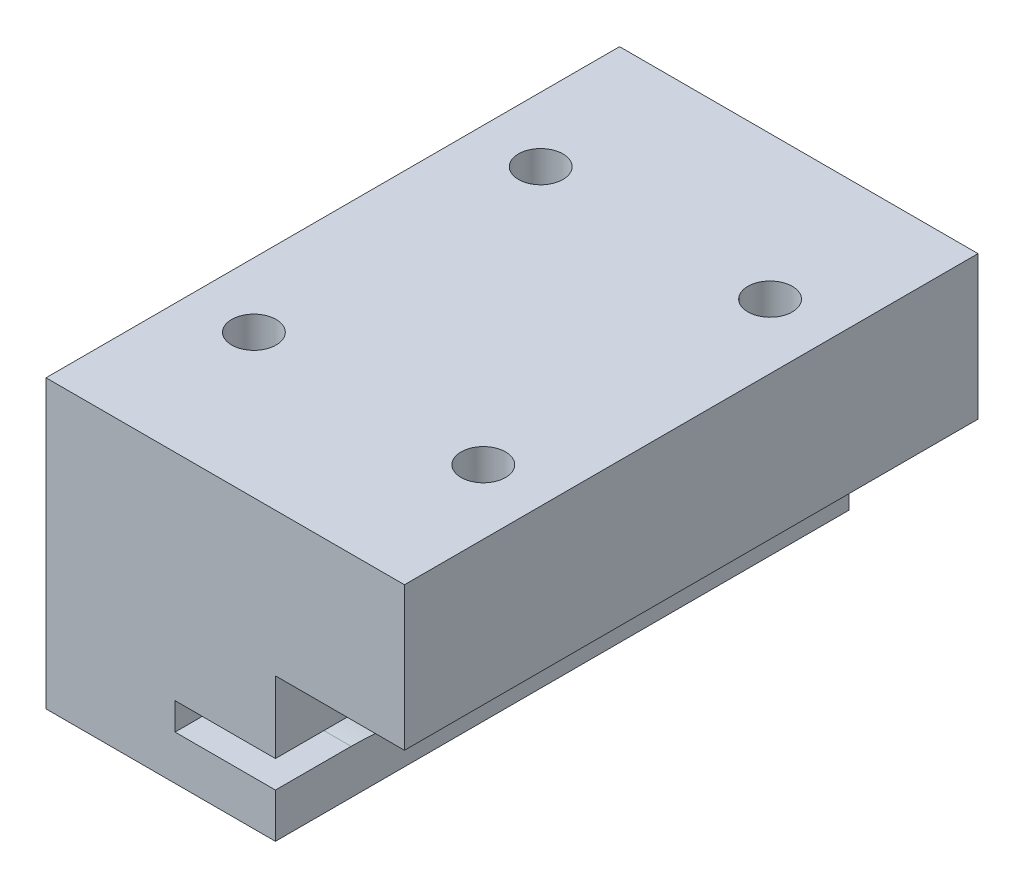
SolidWorks part; units mm, degrees
ref_plane "Front Plane" through (0, 0, 0) normal (0, 0, 1) x (1, 0, 0)
ref_plane "Top Plane" through (0, 0, 0) normal (0, 1, 0) x (1, 0, 0)
ref_plane "Right Plane" through (0, 0, 0) normal (1, 0, 0) x (0, 0, -1)
sketch "Sketch1" plane through (0, 0, 0) normal (0, 0, 1) x (1, 0, 0)
  line L0 (16, 0) -> (0, 0)
  line L1 (0, 0) -> (0, 20)
  line L2 (0, 20) -> (25, 20)
  line L3 (25, 20) -> (25, 10)
  line L4 (25, 10) -> (16, 10)
  line L5 (16, 10) -> (16, 0)
  dimension "D1" = 25
  dimension "D2" = 20
  dimension "D3" = 10
  dimension "D4" = 9
extrude "Boss-Extrude1" add sketch "Sketch1" along normal blind 40
sketch "Sketch2" plane through (0, 20, 0) normal (0, 1, 0) x (1, 0, 0)
  line L0 (0, 0) -> (4.5, 0) construction
  line L1 (25, 0) -> (0, 0) construction
  line L2 (4.5, 0) -> (4.5, -10) construction
  line L3 (25, 0) -> (20.5, 0) construction
  line L4 (20.5, 0) -> (20.5, -10) construction
  line L5 (0, -40) -> (0, 0) construction
  line L6 (25, -40) -> (25, 0) construction
  circle A0 centre (4.5, -10) radius 1.55
  circle A1 centre (20.5, -10) radius 1.55
  circle A2 centre (4.5, -30) radius 1.55
  circle A3 centre (20.5, -30) radius 1.55
  dimension "D5" = 3.1
  dimension "D6" = 3.1
  dimension "D7" = 3.1
  dimension "D8" = 20
  dimension "D9" = 4.5
  dimension "D10" = 20
  dimension "D11" = 4.5
  dimension "D12" = 3.1
  dimension "D1" = 4.5
  dimension "D2" = 4.5
  dimension "D3" = 10
  dimension "D4" = 10
extrude "Cut-Extrude1" cut sketch "Sketch2" against normal through all
sketch "Sketch3" plane through (16, 0, 0) normal (1, 0, 0) x (0, 0, -1)
  line L0 (0, 5) -> (-15, 5) construction
  line L1 (0, 0) -> (0, 10) construction
  line L2 (-40, 5) -> (-25, 5) construction
  line L3 (-40, 0) -> (-40, 10) construction
  line L4 (-40, 20) -> (0, 20) construction
  line L7 (-40, 5) -> (-34.1869, 5)
  line L8 (-40, 5) -> (-40, 3.1)
  line L9 (-40, 3.1) -> (-34.719, 3.1)
  line L11 (0, 5) -> (-5.8131, 5)
  line L12 (0, 5) -> (0, 3.1)
  line L13 (0, 3.1) -> (-5.281, 3.1)
  arc A0 (-26.6515, 1.3568) -> (-27.9281, 7.7251) centre (-25, 5) ccw
  arc A1 (-12.0719, 7.7251) -> (-13.3485, 1.3568) centre (-15, 5) ccw
  arc A2 (-27.9281, 7.7251) -> (-34.1869, 5) centre (-34.1869, 13.55) cw
  arc A3 (-5.8131, 5) -> (-12.0719, 7.7251) centre (-5.8131, 13.55) cw
  arc A4 (-26.6515, 1.3568) -> (-34.719, 3.1) centre (-34.719, -16.44) ccw
  arc A5 (-5.281, 3.1) -> (-13.3485, 1.3568) centre (-5.281, -16.44) ccw
  point P17 (-29, 5)
  point P21 (-11, 5)
  dimension "D5" = 8
  dimension "D6" = 8
  dimension "D7" = 8.55
  dimension "D9" = 8.55
  dimension "D11" = 19.54
  dimension "D12" = 19.54
  dimension "D1" = 15
  dimension "D2" = 15
  dimension "D3" = 15
  dimension "D4" = 15
  dimension "D8" = 1.9
  dimension "D10" = 1.9
extrude "Cut-Extrude2" cut sketch "Sketch3" against normal blind 7
sketch "Sketch4" plane through (9, 0, 0) normal (1, 0, 0) x (0, 0, -1)
  circle A0 centre (-25, 5) radius 2.5
  circle A1 centre (-15, 5) radius 2.5
  dimension "D1" = 5
  dimension "D2" = 5
extrude "Boss-Extrude2" add sketch "Sketch4" along normal blind 7
chamfer "Chamfer1" distance 0.5 angle 45 2 edges at (16, 5, 22.5) (16, 5, 12.5)
sketch "Sketch5" plane through (0, 0, 0) normal (0, -1, 0) x (1, 0, 0)
  line L0 (4.5, 10) -> (9.5, 10) construction
  line L1 (4.5, 10) -> (7.2496, 11.5875) construction
  line L8 (7.2496, 11.5875) -> (4.5, 13.175)
  line L9 (4.5, 13.175) -> (1.7504, 11.5875)
  line L10 (1.7504, 11.5875) -> (1.7504, 8.4125)
  line L11 (1.7504, 8.4125) -> (4.5, 6.825)
  line L12 (4.5, 6.825) -> (7.2496, 8.4125)
  line L13 (7.2496, 8.4125) -> (7.2496, 11.5875)
  line L14 (7.2496, 31.5875) -> (4.5, 33.175)
  line L15 (4.5, 30) -> (7.2496, 31.5875) construction
  line L16 (7.2496, 28.4125) -> (7.2496, 31.5875)
  line L17 (4.5, 26.825) -> (7.2496, 28.4125)
  line L18 (1.7504, 31.5875) -> (1.7504, 28.4125)
  line L19 (4.5, 30) -> (9.5, 30) construction
  line L20 (1.7504, 28.4125) -> (4.5, 26.825)
  line L21 (4.5, 33.175) -> (1.7504, 31.5875)
  line L22 (0, 40) -> (0, 0) construction
  circle A0 centre (4.5, 10) radius 3.175 construction
  circle A1 centre (4.5, 30) radius 3.175 construction
  dimension "D2" = 6.35
  dimension "D5" = 6.35
  dimension "D1" = 5
  dimension "D3" = 30
  dimension "D4" = 30
  dimension "D6" = 20
  dimension "D7" = 4.5
  dimension "D8" = 3.175
extrude "Cut-Extrude3" cut sketch "Sketch5" against normal blind 5
sketch "Sketch6" plane through (0, 10, 0) normal (0, -1, 0) x (1, 0, 0)
  line L0 (20.5, 10) -> (25.5, 10) construction
  line L1 (20.5, 10) -> (23.2496, 11.5875) construction
  line L2 (23.2496, 11.5875) -> (20.5, 13.175)
  line L3 (20.5, 13.175) -> (17.7504, 11.5875)
  line L4 (17.7504, 11.5875) -> (17.7504, 8.4125)
  line L5 (17.7504, 8.4125) -> (20.5, 6.825)
  line L6 (20.5, 6.825) -> (23.2496, 8.4125)
  line L7 (23.2496, 8.4125) -> (23.2496, 11.5875)
  line L8 (20.5, 30) -> (25.5, 30) construction
  line L9 (23.2496, 28.4125) -> (23.2496, 31.5875)
  line L10 (23.2496, 31.5875) -> (20.5, 33.175)
  line L11 (20.5, 33.175) -> (17.7504, 31.5875)
  line L12 (20.5, 26.825) -> (23.2496, 28.4125)
  line L13 (20.5, 30) -> (23.2496, 31.5875) construction
  line L14 (17.7504, 28.4125) -> (20.5, 26.825)
  line L15 (17.7504, 31.5875) -> (17.7504, 28.4125)
  circle A0 centre (20.5, 10) radius 3.175 construction
  circle A1 centre (20.5, 30) radius 3.175 construction
  dimension "D2" = 6.35
  dimension "D6" = 6.35
  dimension "D7" = 20
  dimension "D1" = 5
  dimension "D3" = 30
  dimension "D4" = 5
  dimension "D5" = 30
extrude "Cut-Extrude4" cut sketch "Sketch6" against normal blind 5
